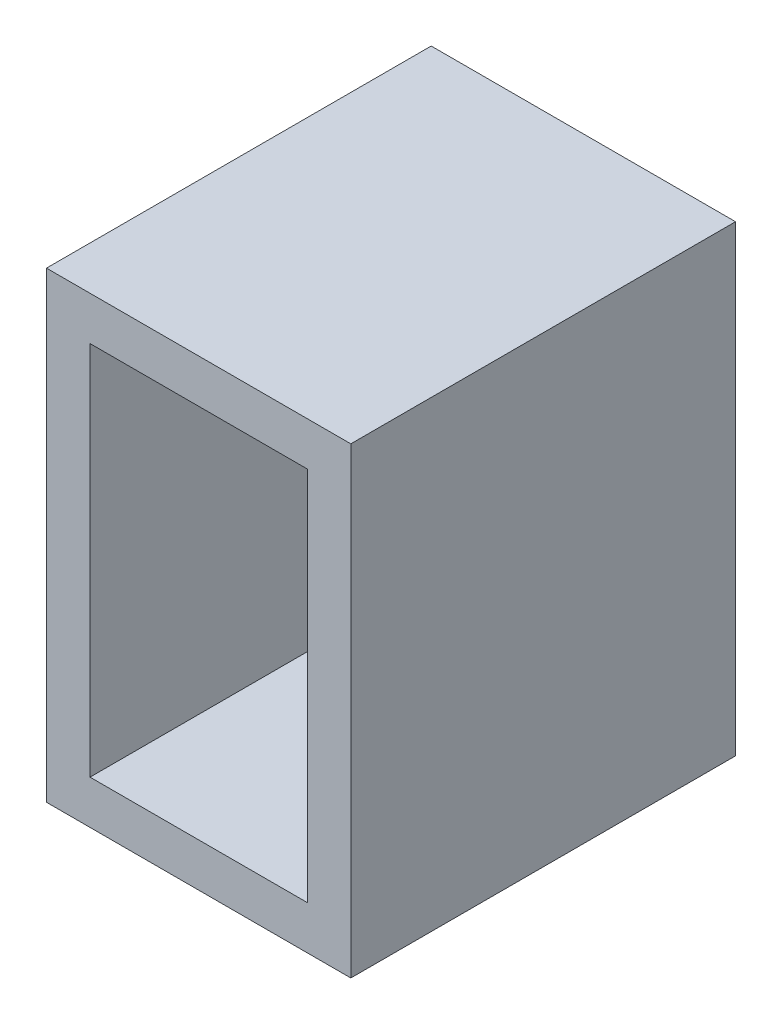
SolidWorks part; units mm, degrees
ref_plane "Alzado" through (0, 0, 0) normal (0, 0, 1) x (1, 0, 0)
ref_plane "Planta" through (0, 0, 0) normal (0, 1, 0) x (1, 0, 0)
ref_plane "Vista lateral" through (0, 0, 0) normal (1, 0, 0) x (0, 0, -1)
sketch "Croquis1" plane through (0, 0, 0) normal (0, 0, 1) x (1, 0, 0)
  line L1 (-9.9691, 26.9473) -> (12.1809, 26.9473)
  line L2 (-9.9691, 26.9473) -> (-9.9691, -6.7227)
  line L3 (-9.9691, -6.7227) -> (12.1809, -6.7227)
  line L4 (12.1809, 26.9473) -> (12.1809, -6.7227)
  dimension "D1" = 22.15
  dimension "D2" = 33.67
extrude "Saliente-Extruir1" add sketch "Croquis1" along normal blind 28
sketch "Croquis2" plane through (0, 0, 28) normal (0, 0, 1) x (1, 0, 0)
  line L0 (12.1809, -6.7227) -> (12.1809, 26.9473) construction
  line L1 (-6.7991, 23.7773) -> (9.0109, 23.7773)
  line L2 (-6.7991, 23.7773) -> (-6.7991, -3.5527)
  line L3 (-6.7991, -3.5527) -> (9.0109, -3.5527)
  line L4 (9.0109, 23.7773) -> (9.0109, -3.5527)
  line L5 (-9.9691, 26.9473) -> (-9.9691, -6.7227) construction
  line L6 (12.1809, 26.9473) -> (-9.9691, 26.9473) construction
  line L7 (-9.9691, -6.7227) -> (12.1809, -6.7227) construction
  dimension "D1" = 3.17
  dimension "D2" = 3.17
  dimension "D3" = 3.17
  dimension "D4" = 3.17
extrude "Cortar-Extruir1" cut sketch "Croquis2" against normal blind 25
